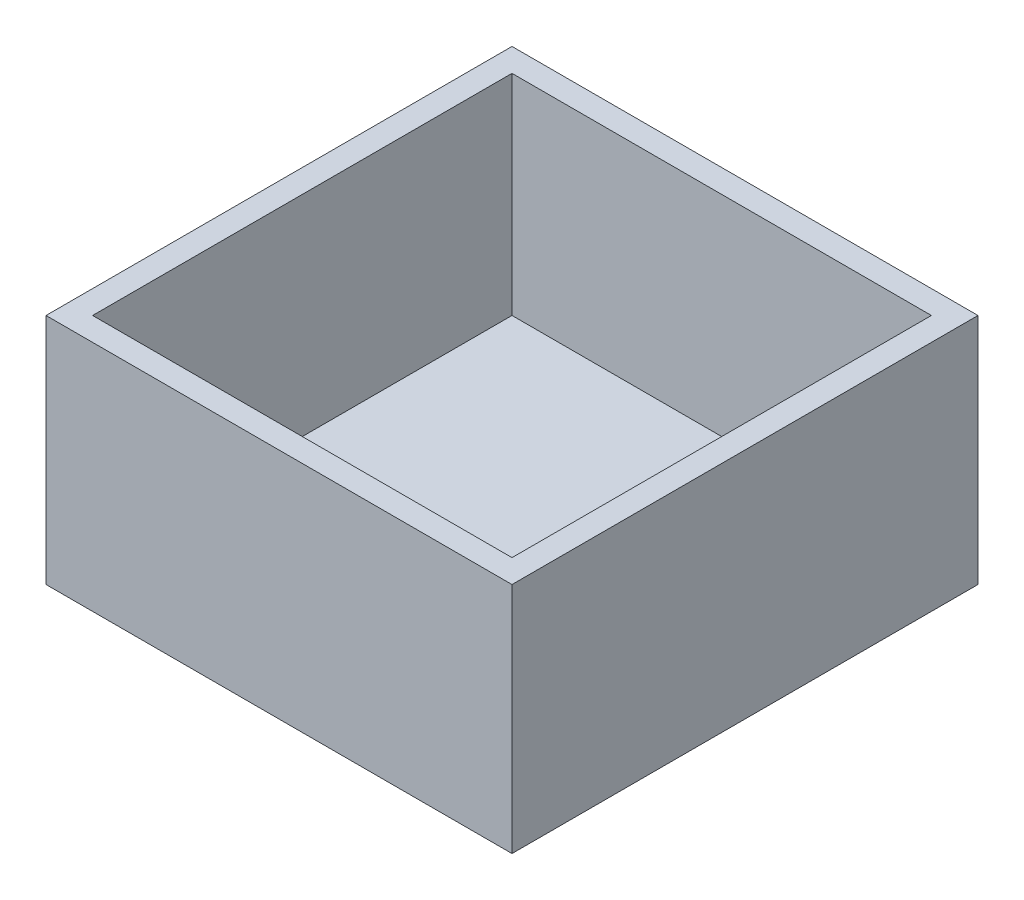
SolidWorks part; units mm, degrees
ref_plane "Front Plane" through (0, 0, 0) normal (0, 0, 1) x (1, 0, 0)
ref_plane "Top Plane" through (0, 0, 0) normal (0, 1, 0) x (1, 0, 0)
ref_plane "Right Plane" through (0, 0, 0) normal (1, 0, 0) x (0, 0, -1)
sketch "Sketch1" plane through (0, 0, 0) normal (0, 1, 0) x (1, 0, 0)
  line L1 (-50, 50) -> (50, 50)
  line L2 (-50, 50) -> (-50, -50)
  line L3 (-50, -50) -> (50, -50)
  line L4 (50, 50) -> (50, -50)
  line L5 (-50, 50) -> (50, -50) construction
  line L6 (-50, -50) -> (50, 50) construction
  point P0 (0, 0)
  dimension "D1" = 100
  dimension "D2" = 100
extrude "Boss-Extrude1" add sketch "Sketch1" along normal blind 50
shell "Shell1" thickness 5
